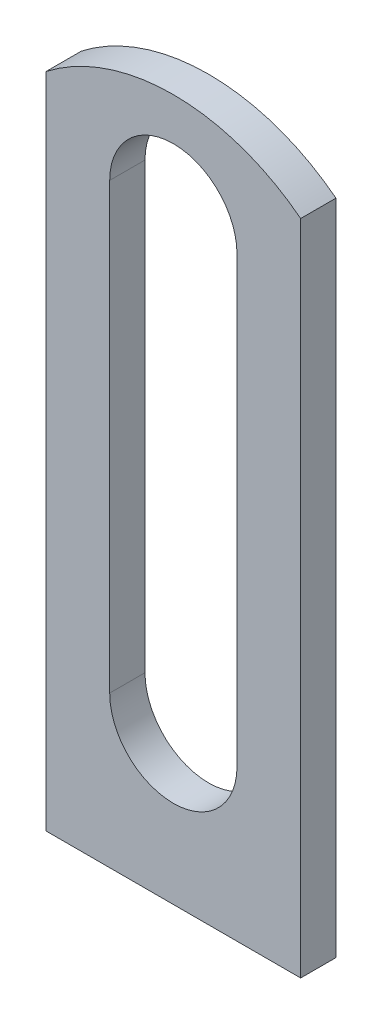
SolidWorks part; units mm, degrees
ref_plane "Front Plane" through (0, 0, 0) normal (0, 0, 1) x (1, 0, 0)
ref_plane "Top Plane" through (0, 0, 0) normal (0, 1, 0) x (1, 0, 0)
ref_plane "Right Plane" through (0, 0, 0) normal (1, 0, 0) x (0, 0, -1)
ref_plane "Plane1" through (0, 0, 2.8) normal (0, 0, 1) x (1, 0, 0)
sketch "Sketch1" plane through (0, 0, 2.8) normal (0, 0, 1) x (1, 0, 0)
  line L0 (15.15, 47.2223) -> (15.15, 12)
  line L1 (5.05, 12) -> (5.05, 47.2223)
  line L3 (0, 52.1796) -> (0, 0)
  line L4 (0, 0) -> (20.2, 0)
  line L5 (20.2, 0) -> (20.2, 52.1796)
  arc A2 (5.05, 47.2223) -> (15.15, 47.2223) centre (10.1, 47.2223) cw
  arc A3 (15.15, 12) -> (5.05, 12) centre (10.1, 12) cw
  arc A8 (0, 52.1796) -> (20.2, 52.1796) centre (10.1, 39.1851) cw
extrude "Boss-Extrude1" add sketch "Sketch1" against normal blind 2.8
